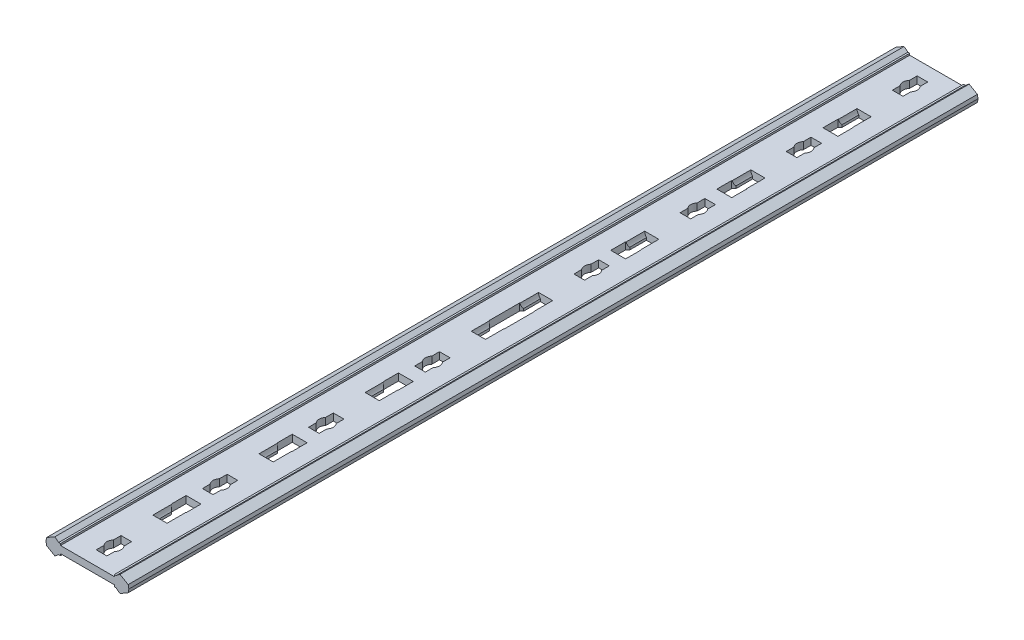
SolidWorks part; units mm, degrees
ref_plane "前视基准面" through (0, 0, 0) normal (0, 0, 1) x (1, 0, 0)
ref_plane "上视基准面" through (0, 0, 0) normal (0, 1, 0) x (1, 0, 0)
ref_plane "右视基准面" through (0, 0, 0) normal (1, 0, 0) x (0, 0, -1)
sketch "草图1" plane through (0, 0, 0) normal (0, 0, 1) x (1, 0, 0)
  line L0 (0, 0) -> (-11.7, 0) construction
  line L1 (-11.7, 0) -> (-11.5237, 1)
  line L2 (-11.5237, 1) -> (-9.2, 2.3416)
  line L3 (-9.2, 2.3416) -> (-8.1, 1.5)
  line L4 (-8.1, 1.5) -> (-7.6, 1.5)
  line L5 (-7.6, 1) -> (7.6, 1)
  line L6 (0, 1) -> (0, 0) construction
  line L7 (-7.6, 1.5) -> (-7.6, 1)
  line L8 (-7.6, -1) -> (7.6, -1)
  line L9 (-7.6, -1.5) -> (-7.6, -1)
  line L10 (-8.1, -1.5) -> (-7.6, -1.5)
  line L11 (-9.2, -2.3416) -> (-8.1, -1.5)
  line L12 (-11.5237, -1) -> (-9.2, -2.3416)
  line L13 (-11.7, 0) -> (-11.5237, -1)
  line L14 (7.6, 1.5) -> (7.6, 1)
  line L15 (8.1, 1.5) -> (7.6, 1.5)
  line L16 (7.6, -1.5) -> (7.6, -1)
  line L17 (8.1, -1.5) -> (7.6, -1.5)
  line L18 (9.2, -2.3416) -> (8.1, -1.5)
  line L19 (9.2, 2.3416) -> (8.1, 1.5)
  line L20 (11.5237, -1) -> (9.2, -2.3416)
  line L21 (11.5237, 1) -> (9.2, 2.3416)
  line L22 (11.7, 0) -> (11.5237, -1)
  line L23 (11.7, 0) -> (11.5237, 1)
  point P19 (0, -1)
  dimension "D1" = 11.7
  dimension "D2" = 80
  dimension "D3" = 1
  dimension "D4" = 30
  dimension "D5" = 2.5
  dimension "D6" = 7.6
  dimension "D7" = 1
  dimension "D8" = 0.5
  dimension "D9" = 0.5
extrude "凸台-拉伸1" add sketch "草图1" along normal blind 120
sketch "草图2" plane through (0, 1, 0) normal (0, 1, 0) x (1, 0, 0)
  line L0 (0, 0) -> (0, -9.5) construction
  line L1 (0, -9.5) -> (0, -22.5) construction
  line L2 (-2.1, 0) -> (-2.1, -9.5)
  line L3 (2.1, 0) -> (2.1, -9.5)
  line L4 (-2.1, 0) -> (2.1, 0)
  line L5 (-2.1, -9.5) -> (2.1, -9.5)
  line L6 (1.5, -19) -> (-1.5, -19)
  line L7 (1.5, -19) -> (1.5, -21.1771)
  line L8 (-1.5, -19) -> (-1.5, -21.1771)
  line L9 (1.5, -26) -> (-1.5, -26)
  line L10 (1.5, -19) -> (-1.5, -26) construction
  line L11 (-1.5, -19) -> (1.5, -26) construction
  line L12 (-1.5, -23.8229) -> (-1.5, -26)
  line L13 (1.5, -23.8229) -> (1.5, -26)
  arc A0 (-1.5, -21.1771) -> (-1.5, -23.8229) centre (0, -22.5) ccw
  arc A1 (1.5, -23.8229) -> (1.5, -21.1771) centre (0, -22.5) ccw
  dimension "D5" = 4
  dimension "D1" = 9.5
  dimension "D4" = 13
  dimension "D6" = 3
  dimension "D7" = 7
  dimension "D2" = 2.1
  dimension "D3" = 2.1
extrude "切除-拉伸1" cut sketch "草图2" against normal up to next
sketch "草图3" plane through (0, 0, 9.5) normal (0, 0, -1) x (-1, 0, 0)
  line L1 (0, 0) -> (0, 1) construction
  line L3 (2.1, 1) -> (-2.1, 1) construction
  line L4 (-2, 1) -> (-2.1, 1)
  line L5 (-2.1, 1) -> (-2.1, -1)
  line L6 (-2.1, -1) -> (-1.5, -1)
  line L7 (-2.1, -1) -> (2.1, -1) construction
  line L8 (-1.5, -1) -> (-1.5, -0.3229)
  line L9 (1.5, -1) -> (1.5, -0.3229)
  line L10 (2.1, -1) -> (1.5, -1)
  line L11 (2.1, 1) -> (2.1, -1)
  line L12 (2, 1) -> (2.1, 1)
  arc A0 (-2, 1) -> (-1.5, -0.3229) centre (0, 1) ccw
  arc A1 (2, 1) -> (1.5, -0.3229) centre (0, 1) cw
  dimension "D1" = 4
  dimension "D2" = 0.6
extrude "凸台-拉伸2" add sketch "草图3" along normal blind 5.3
sketch "草图4" plane through (0, -1, 0) normal (0, -1, 0) x (1, 0, 0)
  line L0 (-2.1, 4.2) -> (-1.5, 4.2)
  line L1 (-1.5, 4.2) -> (-1.5, 4.8)
  line L2 (-1.5, 4.2) -> (-1.5, 9.5) construction
  line L3 (-1.5, 4.8) -> (-2.1, 4.2)
  line L4 (1.5, 4.2) -> (2.1, 4.2)
  line L5 (2.1, 4.2) -> (1.5, 4.8)
  line L6 (1.5, 4.2) -> (1.5, 9.5) construction
  line L7 (1.5, 4.8) -> (1.5, 4.2)
  dimension "D1" = 0.6
  dimension "D2" = 0.6
extrude "切除-拉伸2" cut sketch "草图4" against normal up to next
pattern_linear "阵列(线性)1" count 4 spacing 30 along (0, 0, 1) of "切除-拉伸1", "凸台-拉伸2", "切除-拉伸2"
mirror "镜向1" about plane through (0, 0, 0) normal (0, 0, 1) of "凸台-拉伸1", "阵列(线性)1", "切除-拉伸1", "凸台-拉伸2", "切除-拉伸2"
